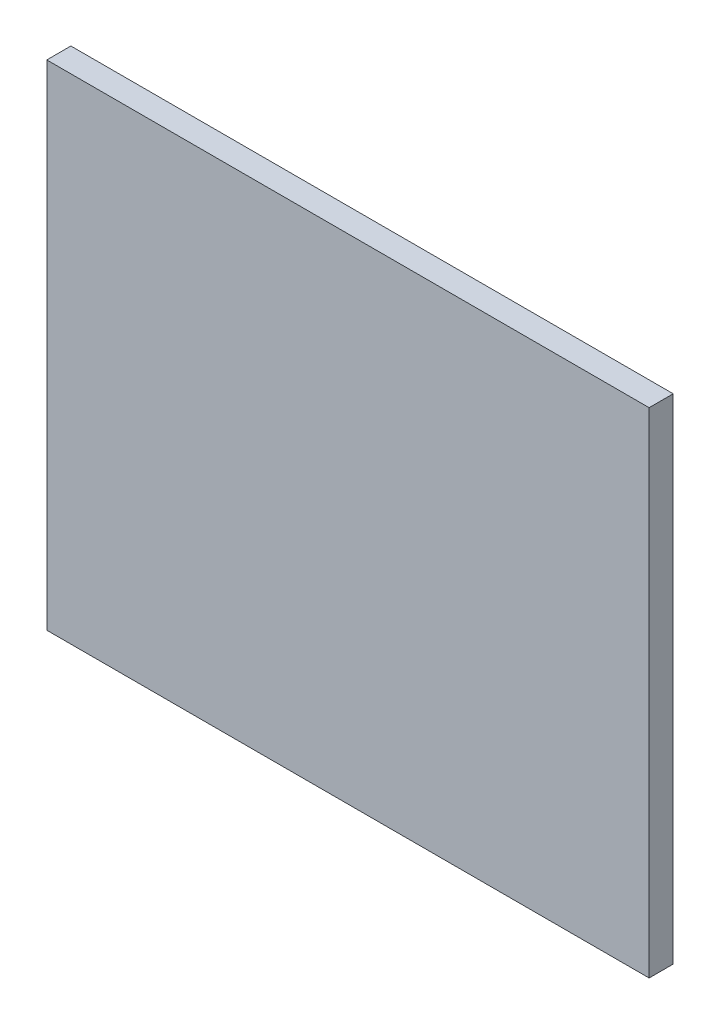
SolidWorks part; units mm, degrees
ref_plane "Front Plane" through (0, 0, 0) normal (0, 0, 1) x (1, 0, 0)
ref_plane "Top Plane" through (0, 0, 0) normal (0, 1, 0) x (1, 0, 0)
ref_plane "Right Plane" through (0, 0, 0) normal (1, 0, 0) x (0, 0, -1)
sketch "Sketch2" plane through (0, 0, 0) normal (0, 0, 1) x (1, 0, 0)
  line L1 (0, 0) -> (500, 0)
  line L2 (0, 0) -> (0, -410)
  line L3 (0, -410) -> (500, -410)
  line L4 (500, 0) -> (500, -410)
  dimension "D1" = 500
  dimension "D2" = 410
extrude "Boss-Extrude1" add sketch "Sketch2" along normal blind 20
